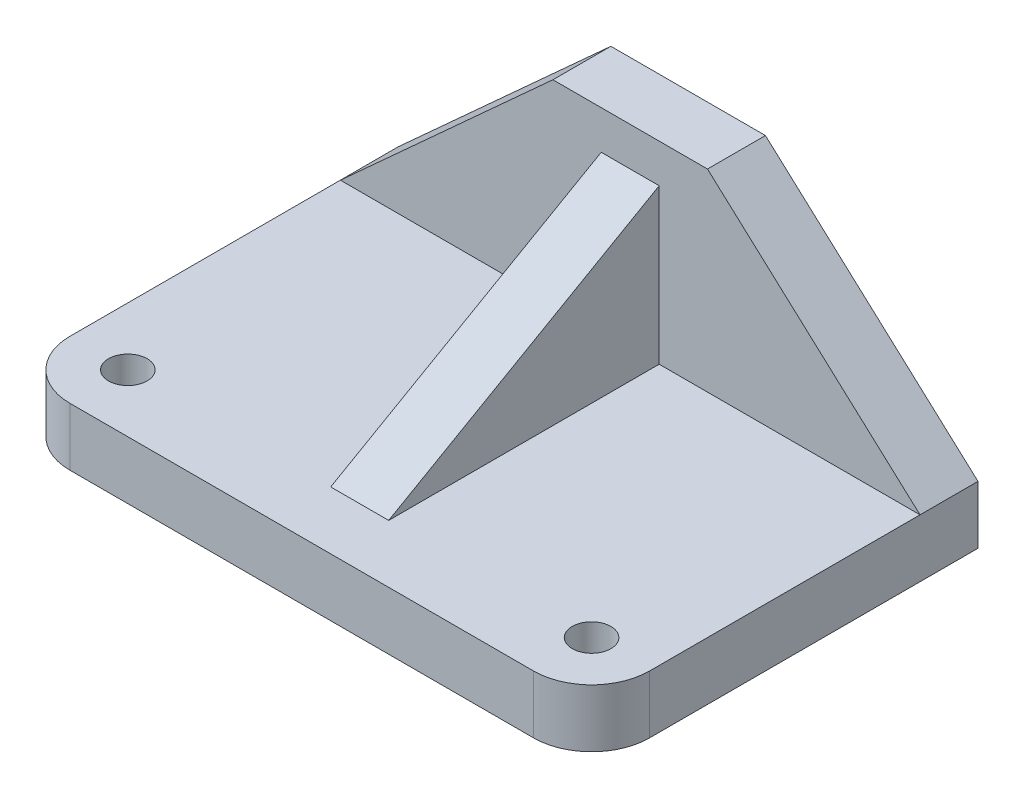
SolidWorks part; units mm, degrees
ref_plane "前视基准面" through (0, 0, 0) normal (0, 0, 1) x (1, 0, 0)
ref_plane "上视基准面" through (0, 0, 0) normal (0, 1, 0) x (1, 0, 0)
ref_plane "右视基准面" through (0, 0, 0) normal (1, 0, 0) x (0, 0, -1)
sketch "草图1" plane through (0, 0, 0) normal (0, 0, 1) x (1, 0, 0)
  line L0 (-79.5796, 0) -> (89.0785, 0)
  line L1 (110, 0) -> (-110, 0) construction
sketch "草图2" plane through (0, 0, 0) normal (0, 1, 0) x (1, 0, 0)
  line L0 (0, 54.0878) -> (0, -55.4537)
  line L1 (0, -61.1647) -> (0, 61.1647) construction
sketch "草图3" plane through (0, 0, 0) normal (0, 1, 0) x (1, 0, 0)
  line L1 (-150, 100) -> (150, 100)
  line L2 (-150, 100) -> (-150, -100)
  line L3 (-150, -100) -> (150, -100)
  line L4 (150, 100) -> (150, -100)
  line L5 (0, -100) -> (0, 100) construction
  line L6 (-150, 0) -> (150, 0) construction
  point P0 (0, 0)
  dimension "D1" = 300
  dimension "D2" = 200
sketch "草图4" plane through (0, 0, 0) normal (0, 1, 0) x (1, 0, 0)
  line L2 (0, -61.1647) -> (0, 61.1647) construction
  circle A0 centre (-120, -70) radius 10
  circle A1 centre (120, -70) radius 10
  point P2 (0, 0)
extrude "凸台-拉伸1" add sketch "草图3" along normal blind 30
fillet "圆角1" radius 30 1 edges at (-150, 15, 100)
fillet "圆角2" radius 30 1 edges at (150, 15, 100)
ref_plane "基准面1" through (0, 0, -100) normal (0, 0, -1) x (-1, 0, 0)
sketch "草图5" plane through (0, 0, -100) normal (0, 0, -1) x (-1, 0, 0)
  line L3 (-150, 30) -> (150, 30) construction
  line L5 (-150, 30) -> (150, 30)
  line L6 (-40, 130) -> (40, 130)
  line L7 (0, 61.1647) -> (0, -61.1647) construction
  line L8 (-150, 30) -> (-40, 130)
  line L9 (40, 130) -> (150, 30)
  point P9 (0, 130)
  dimension "D1" = 0
extrude "凸台-拉伸2" add sketch "草图5" against normal blind 30
extrude "切除-拉伸1" cut sketch "草图4" along normal blind 30 contours A0 | A1
ref_plane "基准面2" through (0, 30, 0) normal (0, 1, 0) x (1, 0, 0)
sketch "草图7" plane through (0, 0, 0) normal (1, 0, 0) x (0, 0, -1)
  line L2 (70, 111.2086) -> (70, 30) construction
  line L3 (93.5, 30) -> (-93.5, 30) construction
  line L4 (-70, 30) -> (-70, 0) construction
  line L5 (70, 30) -> (100, 30) construction
  line L6 (70, 130) -> (70, 30) construction
  line L7 (-70, 30) -> (70, 110)
  line L8 (70, 110) -> (70, 30)
  line L9 (70, 30) -> (-70, 30)
  point P0 (-70, 30)
  point P1 (70, 30)
  point P2 (70, 110)
  point P6 (70, 130)
extrude "凸台-拉伸3" add sketch "草图7" along normal mid plane 30
